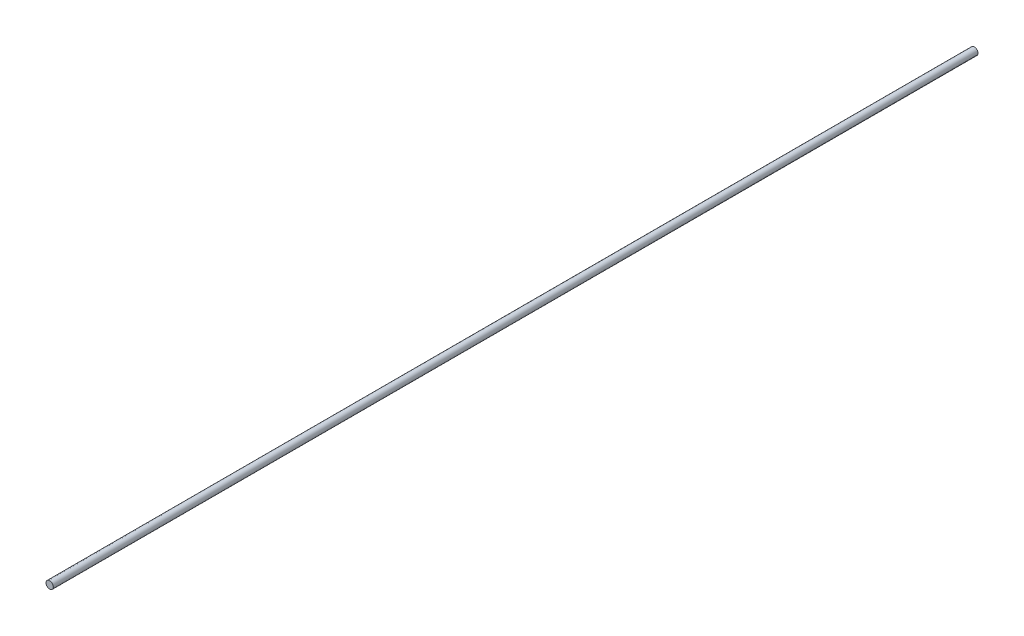
SolidWorks part; units mm, degrees
ref_plane "Front Plane" through (0, 0, 0) normal (0, 0, 1) x (1, 0, 0)
ref_plane "Top Plane" through (0, 0, 0) normal (0, 1, 0) x (1, 0, 0)
ref_plane "Right Plane" through (0, 0, 0) normal (1, 0, 0) x (0, 0, -1)
sketch "Sketch1" plane through (0, 0, 0) normal (1, 0, 0) x (0, 0, -1)
  line L1 (0, 0) -> (190, 0)
  line L2 (0, 0) -> (0, 0.75)
  line L3 (0, 0.75) -> (190, 0.75)
  line L4 (190, 0) -> (190, 0.75)
  dimension "D1" = 0.75
  dimension "D2" = 190
revolve "Revolve1" add sketch "Sketch1" angle 360 about L1
